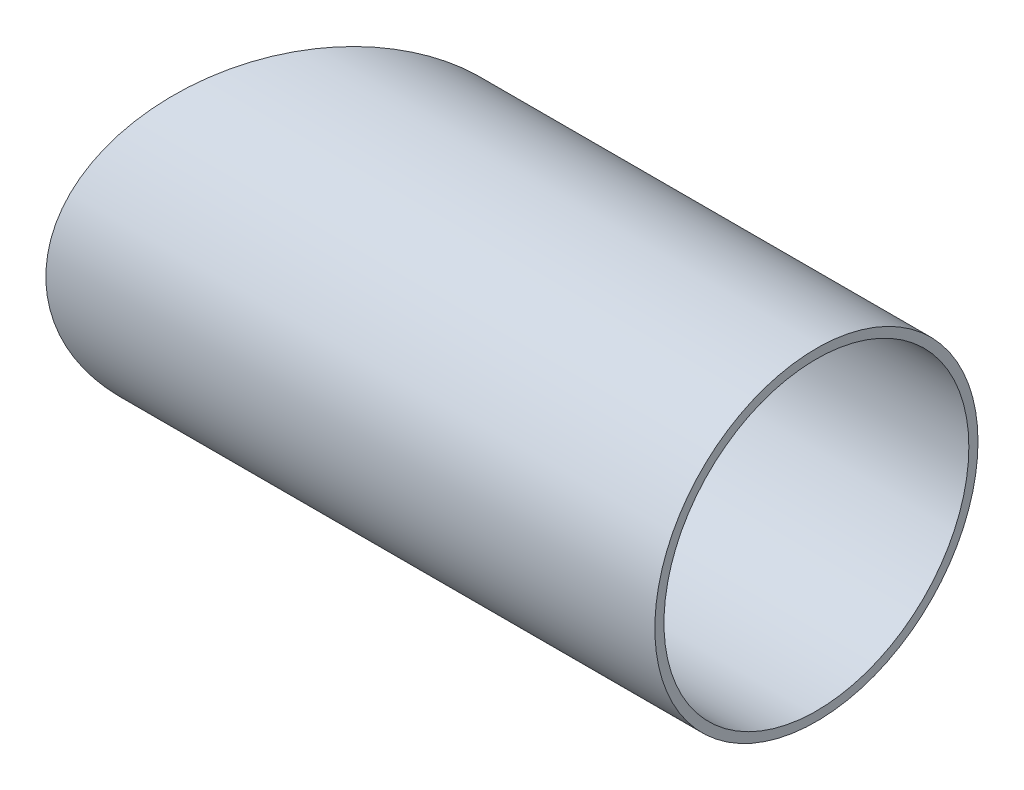
SolidWorks part; units mm, degrees
ref_plane "Front Plane" through (0, 0, 0) normal (0, 0, 1) x (1, 0, 0)
ref_plane "Top Plane" through (0, 0, 0) normal (0, 1, 0) x (1, 0, 0)
ref_plane "Right Plane" through (0, 0, 0) normal (1, 0, 0) x (0, 0, -1)
sketch "Sketch2" plane through (0, 0, 0) normal (0, 1, 0) x (1, 0, 0)
  line L1 (-404.1452, -700) -> (404.1452, -700)
  line L2 (404.1452, -700) -> (808.2904, 0)
  line L3 (808.2904, 0) -> (404.1452, 700)
  line L4 (404.1452, 700) -> (-404.1452, 700)
  line L5 (-404.1452, 700) -> (-808.2904, 0)
  line L6 (-808.2904, 0) -> (-404.1452, -700)
  circle A0 centre (0, 0) radius 700 construction
  dimension "D1" = 700
sketch "Sketch3" plane through (0, 0, 0) normal (1, 0, 0) x (0, 0, -1)
  circle A0 centre (-700, 0) radius 50
  circle A1 centre (-700, 0) radius 53
  dimension "D1" = 100
  dimension "D2" = 3
sweep "Sweep1" add profiles "Sketch3" path "Sketch2"
sketch "Sketch4" plane through (0, 0, 0) normal (0, 1, 0) x (1, 0, 0)
  line L0 (-235, -407.0319) -> (-487.5, -844.3748)
  line L1 (0, -975) -> (0, 0) construction
  line L2 (-235, -407.0319) -> (-235, -946.2558)
  line L3 (-235, -407.0319) -> (0, 0) construction
  circle A0 centre (0, 0) radius 975 construction
  dimension "D1" = 1950
  dimension "D2" = 235
split "Split1" trim tools "Sketch4" bodies to split 101 resulting bodies 103
